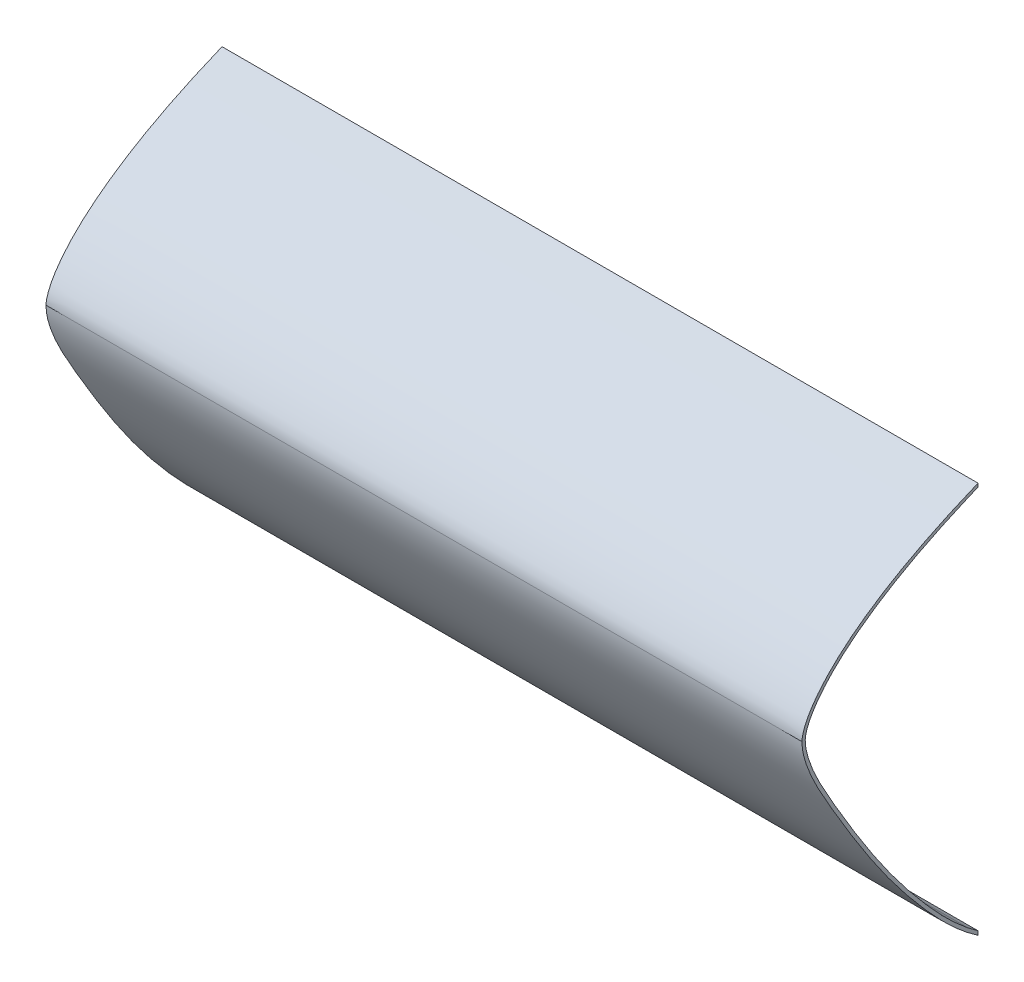
SolidWorks part; units mm, degrees
material "CARBON FIBERR"
ref_plane "Front" through (0, 0, 0) normal (0, 0, 1) x (1, 0, 0)
ref_plane "Top" through (0, 0, 0) normal (0, 1, 0) x (1, 0, 0)
ref_plane "Right" through (0, 0, 0) normal (1, 0, 0) x (0, 0, -1)
sketch "Sketch1" plane through (34.925, 0, 0) normal (-1, 0, 0) x (0, 0, 1)
  line L0 (-53.975, -25.2967) -> (-53.975, -11.4653) construction
  line L1 (-53.975, -78.4194) -> (-53.975, 41.651)
  spline S0 degree 3 poles (4981.8342, -396.5609) (-91.8087, 63.6859) (5.3281, 25.3313) (-0.5702, -4.3968) (-2.5361, -10.6164) (-7.9982, -20.5501) (-16.1137, -34.185) (-25.7513, -48.9002) (-36.932, -62.9388) (-49.3364, -75.9186) (-65.2269, -85.625) (-84.4528, -91.7174) (-106.8521, -96.1515) (-132.5109, -98.5722) (-161.1944, -99.0924) (-192.7613, -97.7042) (-227.0382, -94.5118) (-263.8348, -89.6638) (-302.9215, -83.3884) (-344.0178, -75.9778) (-386.7768, -67.7807) (-430.7746, -59.2023) (-475.4963, -50.6638) (-520.3353, -42.6036) (-564.5889, -35.4228) (-607.4709, -29.4733) (-648.1275, -25.0145) (-685.6676, -22.1862) (-719.1968, -21.0048) (-747.8303, -21.2786) (-770.6884, -22.8547) (-787.0914, -25.0735) (-876.8677, -41.1472) (-945.9809, -128.2669) (-2071.1001, 4801.8764) knots -0.096815 -0.096815 -0.096815 -0.096815 0.001821 0.004613 0.009135 0.024676 0.044153 0.064937 0.086321 0.107138 0.1276 0.150893 0.177565 0.207668 0.241222 0.278203 0.318526 0.362031 0.408465 0.457479 0.508614 0.561296 0.614835 0.668438 0.721214 0.772202 0.820393 0.864766 0.904324 0.938132 0.965242 0.98469 0.99621 1.28526 1.28526 1.28526 1.28526 only from (0, 0) to (-802.1511, -28.0117) construction
  spline S1 degree 3 poles (595.9868, -4824.44) (-948.5227, 15.9159) (-856.0345, -49.5998) (-789.3572, -23.4586) (-777.0615, -18.6436) (-760.5817, -13.0401) (-739.9968, -7.1233) (-715.5772, -0.3798) (-687.647, 7.013) (-656.6835, 14.9584) (-623.1589, 23.2583) (-587.5492, 31.6944) (-550.3192, 40.0262) (-511.9148, 48.0016) (-472.7617, 55.3745) (-433.2622, 61.9128) (-393.7959, 67.4048) (-354.7199, 71.6552) (-316.357, 74.5357) (-278.9313, 75.7536) (-242.6994, 75.3938) (-207.8706, 73.5467) (-174.7468, 70.259) (-143.6014, 65.7682) (-114.7621, 60.1875) (-88.5345, 53.6285) (-65.199, 46.2382) (-45.0006, 38.1339) (-28.1586, 29.5092) (-14.871, 20.5578) (-6.1442, 12.3133) (-1.9481, 6.1765) (-0.6391, 3.0841) (-0.217, 1.668) (3.0517, -15.0089) (-59.3046, -37.645) (4977.732, 428.207) knots -0.226708 -0.226708 -0.226708 -0.226708 0.003802 0.014472 0.030564 0.051299 0.077028 0.107574 0.142399 0.180921 0.222525 0.266591 0.312515 0.35971 0.407632 0.455773 0.503669 0.550901 0.597096 0.641976 0.685512 0.727353 0.767354 0.805169 0.840471 0.872937 0.902335 0.928425 0.951113 0.970253 0.985871 0.993982 0.996753 0.997907 0.999293 1.057589 1.057589 1.057589 1.057589 only from (-802.1511, -28.0117) to (0, 0) construction
  spline S2 degree 3 poles (0, 0) (-0.0175, -0.519) (-0.0617, -1.8338) (-0.5702, -4.3968) (-2.5361, -10.6164) (-7.9982, -20.5501) (-16.1137, -34.185) (-25.7513, -48.9002) (-36.932, -62.9388) (-49.3364, -75.9186) (-65.2269, -85.625) (-84.4528, -91.7174) (-106.8521, -96.1515) (-132.5109, -98.5722) (-161.1944, -99.0924) (-192.7613, -97.7042) (-227.0382, -94.5118) (-263.8348, -89.6638) (-302.9215, -83.3884) (-344.0178, -75.9778) (-386.7768, -67.7807) (-430.7746, -59.2023) (-475.4963, -50.6638) (-520.3353, -42.6036) (-564.5889, -35.4228) (-607.4709, -29.4733) (-648.1275, -25.0145) (-685.6676, -22.1862) (-719.1968, -21.0048) (-747.8303, -21.2786) (-770.6884, -22.8547) (-787.0914, -25.0735) (-796.8423, -26.8193) (-801.0977, -27.7751) (-802.1511, -28.0117) knots 0 0 0 0 0.001821 0.004613 0.009135 0.024676 0.044153 0.064937 0.086321 0.107138 0.1276 0.150893 0.177565 0.207668 0.241222 0.278203 0.318526 0.362031 0.408465 0.457479 0.508614 0.561296 0.614835 0.668438 0.721214 0.772202 0.820393 0.864766 0.904324 0.938132 0.965242 0.98469 0.99621 1 1 1 1
  spline S3 degree 3 poles (-802.1511, -28.0117) (-801.1372, -27.7105) (-797.2784, -26.5642) (-789.3572, -23.4586) (-777.0615, -18.6436) (-760.5817, -13.0401) (-739.9968, -7.1233) (-715.5772, -0.3798) (-687.647, 7.013) (-656.6835, 14.9584) (-623.1589, 23.2583) (-587.5492, 31.6944) (-550.3192, 40.0262) (-511.9148, 48.0016) (-472.7617, 55.3745) (-433.2622, 61.9128) (-393.7959, 67.4048) (-354.7199, 71.6552) (-316.357, 74.5357) (-278.9313, 75.7536) (-242.6994, 75.3938) (-207.8706, 73.5467) (-174.7468, 70.259) (-143.6014, 65.7682) (-114.7621, 60.1875) (-88.5345, 53.6285) (-65.199, 46.2382) (-45.0006, 38.1339) (-28.1586, 29.5092) (-14.871, 20.5578) (-6.1442, 12.3133) (-1.9481, 6.1765) (-0.6391, 3.0841) (-0.217, 1.668) (-0.0426, 0.7778) (-0.0107, 0.1963) (0, 0) knots 0 0 0 0 0.003802 0.014472 0.030564 0.051299 0.077028 0.107574 0.142399 0.180921 0.222525 0.266591 0.312515 0.35971 0.407632 0.455773 0.503669 0.550901 0.597096 0.641976 0.685512 0.727353 0.767354 0.805169 0.840471 0.872937 0.902335 0.928425 0.951113 0.970253 0.985871 0.993982 0.996753 0.997907 0.999293 1 1 1 1
  spline S4 degree 1 poles (-789.2908, -24.5075) (-1.0009, -0.0106) knots 0 0 1 1 construction
  spline S5 degree 1 poles (-1.0009, -0.0106) (-789.2908, -24.5075) knots 0 0 1 1 construction
  spline S6 degree 3 poles (-789.2908, -24.5075) (-785.3163, -22.9509) (-777.3554, -19.854) (-761.2394, -14.2813) (-740.7218, -8.356) (-715.9964, -1.5357) (-691.2078, 5.039) (-666.3726, 11.4509) (-633.2067, 19.788) (-591.6453, 29.7876) (-541.5821, 40.9551) (-491.2968, 51.0591) (-440.7669, 59.8425) (-389.9856, 66.9978) (-347.468, 71.3203) (-313.3654, 73.5459) (-279.214, 74.78) (-245.0298, 74.5204) (-210.9104, 72.6538) (-185.3864, 70.3744) (-159.9555, 67.2138) (-134.6626, 63.1156) (-109.5715, 57.9457) (-88.911, 52.5848) (-72.6183, 47.5158) (-60.5547, 43.2587) (-48.7006, 38.47) (-37.1259, 33.0527) (-27.8301, 27.8819) (-20.7191, 23.2421) (-15.6145, 19.4551) (-10.7867, 15.3221) (-6.4295, 10.7521) (-3.3298, 6.5207) (-1.7664, 3.2894) (-1.2346, 1.6296) (-1.0709, 0.8085) (-1.0227, 0.3736) (-1.0078, 0.114) (-1.0009, -0.0106) knots 0.015898 0.015898 0.015898 0.015898 0.031274 0.04665 0.077401 0.108153 0.138904 0.169656 0.200407 0.26191 0.323413 0.384916 0.446419 0.507923 0.569426 0.600177 0.630929 0.692432 0.723183 0.753935 0.784686 0.815438 0.846189 0.876941 0.892316 0.907692 0.923068 0.938444 0.95382 0.961507 0.969195 0.976883 0.984571 0.992259 0.996103 0.998025 0.998986 0.999466 0.999947 0.999947 0.999947 0.999947
  spline S7 degree 3 poles (-1.0009, -0.0106) (-1.0099, -0.2779) (-1.0289, -0.8234) (-1.1028, -1.8259) (-1.4168, -3.5972) (-2.4522, -7.2032) (-4.5577, -12.1314) (-7.6943, -17.8738) (-12.0815, -25.4664) (-17.7322, -34.7965) (-24.9199, -45.7682) (-31.4576, -54.481) (-37.0476, -61.1825) (-42.8536, -67.72) (-50.6545, -75.2474) (-61.6337, -82.3376) (-73.6522, -87.3558) (-86.2831, -90.8757) (-99.0883, -93.5961) (-116.3556, -96.1813) (-138.1724, -97.7923) (-164.4147, -97.9546) (-190.6442, -96.7472) (-216.8104, -94.5068) (-242.9011, -91.4628) (-277.5889, -86.5748) (-320.7803, -79.293) (-372.4416, -69.5597) (-424.0475, -59.4829) (-475.6974, -49.5822) (-527.4768, -40.324) (-579.4491, -32.1431) (-631.6563, -25.5197) (-675.3681, -21.7598) (-710.4397, -20.2592) (-736.775, -20.0353) (-763.1229, -21.0632) (-780.614, -23.101) (-789.2908, -24.5075) knots 0.000052 0.000052 0.000052 0.000052 0.001013 0.001974 0.003897 0.007743 0.015433 0.023124 0.030815 0.046197 0.061579 0.07696 0.084651 0.092342 0.107724 0.123105 0.138487 0.153869 0.16925 0.184632 0.215396 0.246159 0.276922 0.307686 0.338449 0.369213 0.430739 0.492266 0.553793 0.61532 0.676847 0.738374 0.7999 0.861427 0.892191 0.922954 0.953717 0.984481 0.984481 0.984481 0.984481
  spline M1 degree 3 poles (-1.0009, -0.0106) (-1.0078, 0.114) (-1.0227, 0.3736) (-1.0709, 0.8085) (-1.2346, 1.6296) (-1.7664, 3.2894) (-3.3298, 6.5207) (-6.4295, 10.7521) (-10.7867, 15.3221) (-15.6145, 19.4551) (-20.7191, 23.2421) (-27.8301, 27.8819) (-37.1259, 33.0527) (-48.7006, 38.47) (-60.5547, 43.2587) (-72.6183, 47.5158) (-88.911, 52.5848) (-109.5715, 57.9457) (-134.6626, 63.1156) (-159.9555, 67.2138) (-185.3864, 70.3744) (-210.9104, 72.6538) (-245.0298, 74.5204) (-279.214, 74.78) (-313.3654, 73.5459) (-347.468, 71.3203) (-389.9856, 66.9978) (-440.7669, 59.8425) (-491.2968, 51.0591) (-541.5821, 40.9551) (-591.6453, 29.7876) (-633.2067, 19.788) (-666.3726, 11.4508) (-691.2078, 5.039) (-715.9964, -1.5357) (-740.7218, -8.356) (-761.2394, -14.2813) (-777.3554, -19.854) (-785.3164, -22.9509) (-789.2908, -24.5075) knots 0.015898 0.015898 0.015898 0.015898 0.016379 0.016859 0.01782 0.019742 0.023586 0.031274 0.038962 0.04665 0.054338 0.062025 0.077401 0.092777 0.108153 0.123529 0.138904 0.169656 0.200407 0.231159 0.26191 0.292662 0.323413 0.384916 0.415668 0.446419 0.507923 0.569426 0.630929 0.692432 0.753935 0.815438 0.846189 0.876941 0.907692 0.938444 0.969195 0.984571 0.999947 0.999947 0.999947 0.999947 only from (-1.0009, -0.0106) to (-50.8, 39.2481)
  spline M11 degree 3 poles (-789.2908, -24.5075) (-780.614, -23.101) (-763.1229, -21.0632) (-736.7751, -20.0353) (-710.4397, -20.2592) (-675.3681, -21.7598) (-631.6563, -25.5197) (-579.4491, -32.1431) (-527.4768, -40.324) (-475.6974, -49.5822) (-424.0475, -59.4829) (-372.4416, -69.5597) (-320.7803, -79.293) (-277.5889, -86.5748) (-242.9011, -91.4628) (-216.8104, -94.5068) (-190.6442, -96.7473) (-164.4148, -97.9546) (-138.1724, -97.7923) (-116.3556, -96.1813) (-99.0883, -93.5961) (-86.2831, -90.8757) (-73.6522, -87.3558) (-61.6337, -82.3376) (-50.6545, -75.2474) (-42.8536, -67.72) (-37.0476, -61.1825) (-31.4576, -54.481) (-24.9199, -45.7682) (-17.7322, -34.7965) (-12.0815, -25.4664) (-7.6943, -17.8738) (-4.5577, -12.1314) (-2.4521, -7.2032) (-1.4168, -3.5972) (-1.1028, -1.8259) (-1.0289, -0.8234) (-1.0099, -0.2779) (-1.0009, -0.0106) knots 0.000052 0.000052 0.000052 0.000052 0.030815 0.061579 0.092342 0.123105 0.184632 0.246159 0.307686 0.369213 0.43074 0.492266 0.553793 0.61532 0.646083 0.676847 0.70761 0.738374 0.769137 0.7999 0.815282 0.830664 0.846046 0.861427 0.876809 0.892191 0.899882 0.907572 0.922954 0.938336 0.953718 0.961408 0.969099 0.97679 0.980635 0.982558 0.98352 0.984481 0.984481 0.984481 0.984481 only from (-50.8, -74.825) to (-1.0009, -0.0106)
  dimension "D1" = 1
extrude "Boss-Extrude1" add sketch "Sketch1" against normal up to vertex (231.775 mm away) contours S7 L1 S2 S3 S6 M11 M1
